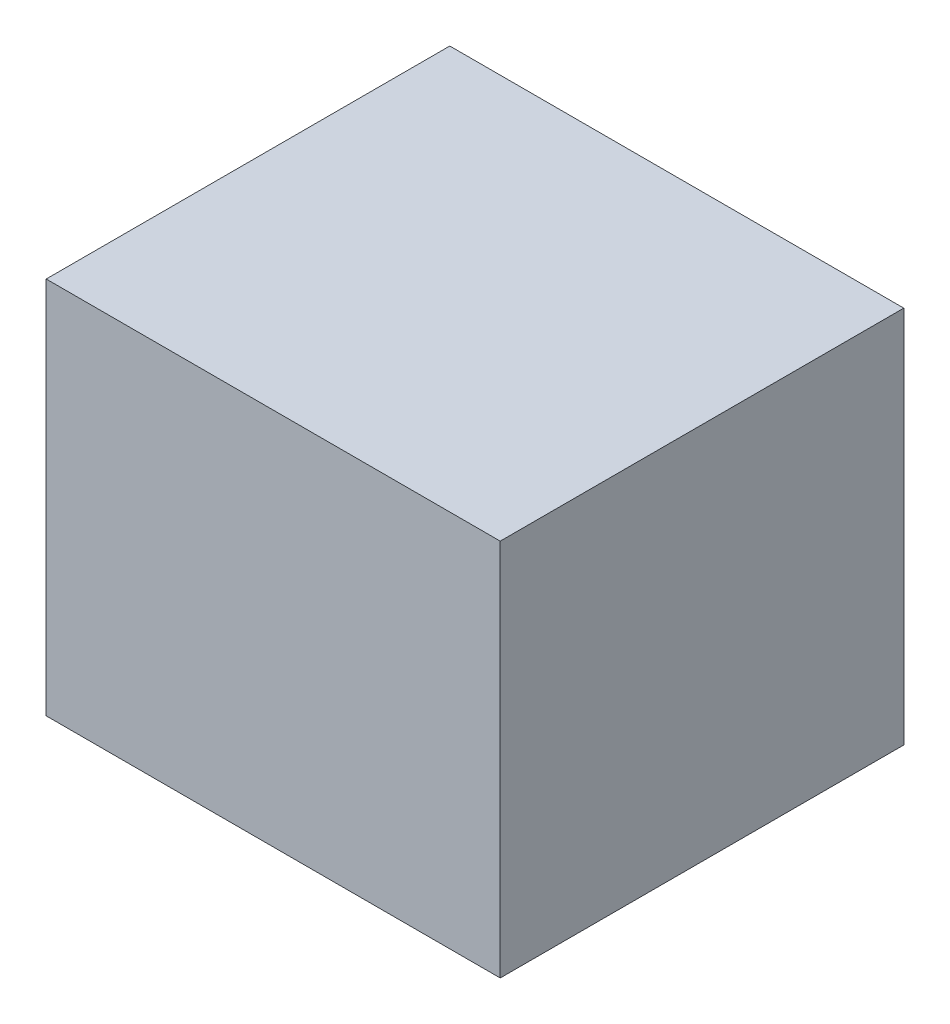
SolidWorks part; units mm, degrees
ref_plane "Front Plane" through (0, 0, 0) normal (0, 0, 1) x (1, 0, 0)
ref_plane "Top Plane" through (0, 0, 0) normal (0, 1, 0) x (1, 0, 0)
ref_plane "Right Plane" through (0, 0, 0) normal (1, 0, 0) x (0, 0, -1)
sketch "Sketch1" plane through (0, 0, 0) normal (0, 1, 0) x (1, 0, 0)
  line L1 (-9, -8) -> (9, -8)
  line L2 (-9, -8) -> (-9, 8)
  line L3 (-9, 8) -> (9, 8)
  line L4 (9, -8) -> (9, 8)
  line L5 (-9, -8) -> (9, 8) construction
  line L6 (-9, 8) -> (9, -8) construction
  point P0 (0, 0)
  dimension "D1" = 18
  dimension "D2" = 16
extrude "Boss-Extrude2" add sketch "Sketch1" along normal blind 15
